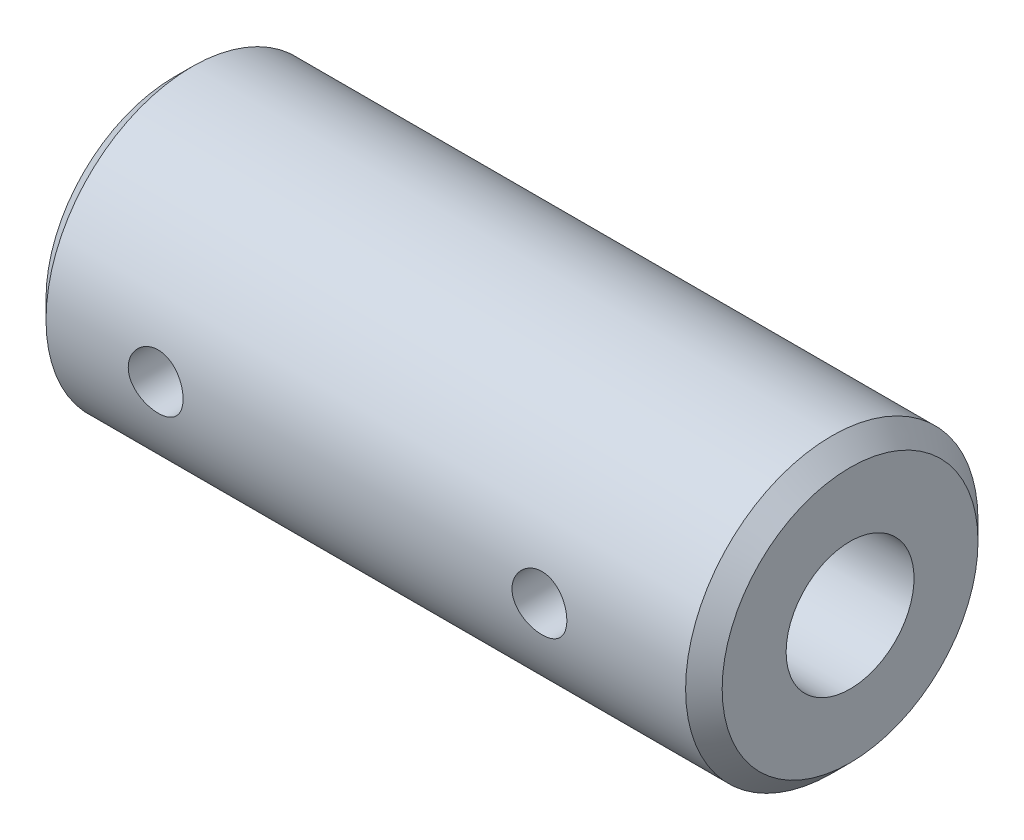
SolidWorks part; units mm, degrees
material "1060-H14"
ref_plane "Plano frontal" through (0, 0, 0) normal (0, 0, 1) x (1, 0, 0)
ref_plane "Plano superior" through (0, 0, 0) normal (0, 1, 0) x (1, 0, 0)
ref_plane "Plano direito" through (0, 0, 0) normal (1, 0, 0) x (0, 0, -1)
sketch "Esboço1" plane through (0, 0, 0) normal (0, 0, 1) x (1, 0, 0)
  line L0 (81.95, -6.93) -> (118.95, -6.93) construction
  line L1 (81.95, -12.93) -> (81.95, -0.93) construction
  line L2 (81.95, -3.93) -> (81.95, 0.07)
  line L3 (82.95, 1.07) -> (117.95, 1.07)
  line L4 (118.95, 0.07) -> (118.95, -3.43)
  line L5 (81.95, -3.93) -> (96.95, -3.93)
  line L6 (97.95, -4.93) -> (97.95, -6.93)
  line L7 (96.7, -3.93) -> (81.95, -3.93) construction
  line L8 (96.95, -3.93) -> (97.95, -4.93)
  line L9 (101.7, -6.93) -> (101.7, -3.93)
  line L10 (101.7, -3.93) -> (102.7, -3.43)
  line L11 (102.7, -3.43) -> (118.95, -3.43)
  line L13 (117.95, 1.07) -> (118.95, 0.07)
  line L14 (81.95, 0.07) -> (82.95, 1.07)
  line L15 (97.95, -6.93) -> (101.7, -6.93)
  point P5 (81.95, 1.07)
  point P6 (118.95, 1.07)
  point P7 (97.95, -3.93)
  dimension "D1" = 37
  dimension "D2" = 16
  dimension "D3" = 16
  dimension "D4" = 7
revolve "Revolução1" add sketch "Esboço1" angle 360 about L0
cosmetic thread "Representação de rosca3" parameters "D2"=8
sketch "Esboço2" plane through (0, 0, 0) normal (0, 0, 1) x (1, 0, 0)
  line L0 (81.95, -6.93) -> (118.95, -6.93) construction
  line L1 (81.95, 0.07) -> (81.95, -13.93) construction
  line L2 (118.95, -13.93) -> (118.95, 0.07) construction
  circle A0 centre (88.95, -6.93) radius 1.5
  circle A1 centre (109.95, -6.93) radius 1.5
  dimension "D1" = 3
  dimension "D3" = 3
  dimension "D4" = 9
  dimension "D2" = 7
extrude "Corte-extrusão1" cut sketch "Esboço2" along normal through all
cosmetic thread "Representação de rosca1" parameters "D1"=5, "D2"=4
cosmetic thread "Representação de rosca2" parameters "D1"=4.2919, "D2"=4
